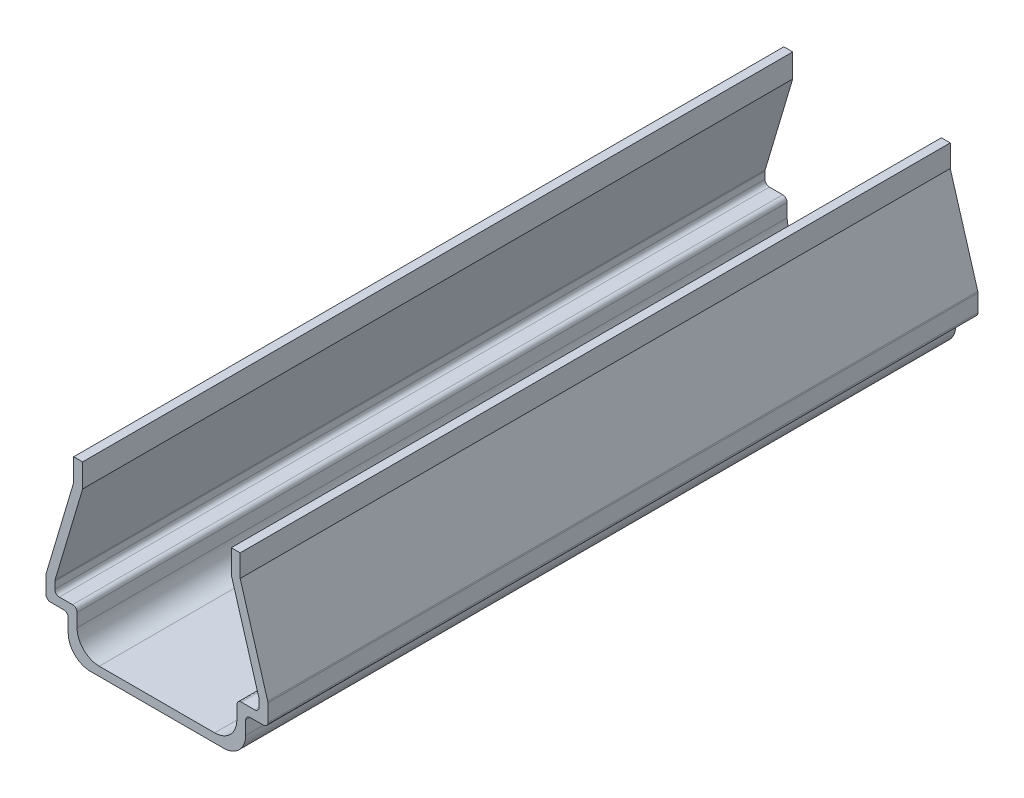
SolidWorks part; units mm, degrees
ref_plane "Front Plane" through (0, 0, 0) normal (0, 0, 1) x (1, 0, 0)
ref_plane "Top Plane" through (0, 0, 0) normal (0, 1, 0) x (1, 0, 0)
ref_plane "Right Plane" through (0, 0, 0) normal (1, 0, 0) x (0, 0, -1)
sketch "Sketch1" plane through (0, 0, 0) normal (0, 0, 1) x (1, 0, 0)
  line L0 (0, 0) -> (0, 7.1478) construction
  line L1 (4, 0) -> (-4, 0)
  line L2 (-4, 0) -> (-4, 1.8)
  line L3 (-4, 1.8) -> (-5, 1.8)
  line L4 (-5, 1.8) -> (-5, 2.8)
  line L5 (4, 0) -> (4, 1.8)
  line L6 (4, 1.8) -> (5, 1.8)
  line L7 (5, 1.8) -> (5, 2.8)
  line L8 (-5, 2.8) -> (-3.75, 7)
  line L9 (-3.75, 7) -> (-3.75, 8)
  line L10 (3.75, 7) -> (3.75, 8)
  line L11 (5, 2.8) -> (3.75, 7)
  point P15 (-1.7894, 3.2119)
  point P16 (-2.8858, 4.2255)
  point P17 (-5, 1.4328)
  point P18 (-3.4029, 5)
  dimension "D1" = 8
  dimension "D2" = 10
  dimension "D3" = 1.8
  dimension "D4" = 8
  dimension "D5" = 1
  dimension "D6" = 1
  dimension "D7" = 7.5
extrude "Extrude-Thin1" add sketch "Sketch1" along normal blind 32 thin
fillet "Fillet1" radius 1 4 edges at (3.6, 0.4, 16) (4, 0, 16) (-4, 0, 16) (-3.6, 0.4, 16)
fillet "Fillet2" radius 0.2 12 edges at (5, 2.8, 16) (4.6, 2.2, 16) (-4.6, 2.7417, 16) (-5, 2.8, 16) (-4.6, 2.2, 16) (5, 1.8, 16) (-5, 1.8, 16) (4.6, 2.7417, 16) (4, 1.8, 16) (3.6, 2.2, 16) (-4, 1.8, 16) (-3.6, 2.2, 16)
